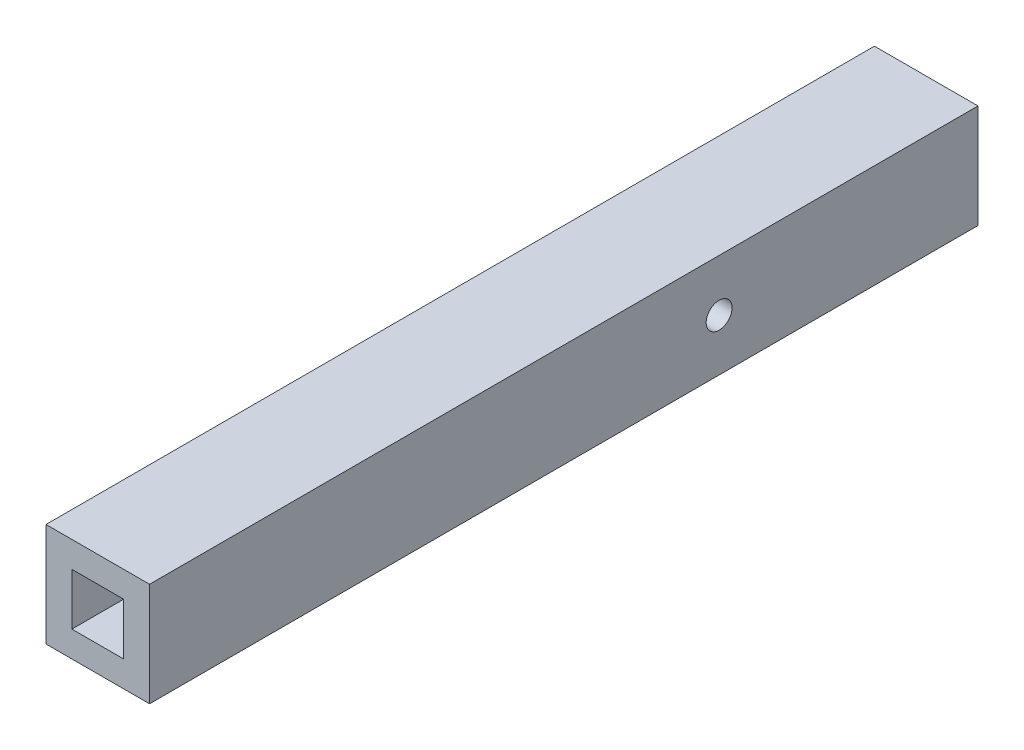
SolidWorks part; units mm, degrees
ref_plane "Front Plane" through (0, 0, 0) normal (0, 0, 1) x (1, 0, 0)
ref_plane "Top Plane" through (0, 0, 0) normal (0, 1, 0) x (1, 0, 0)
ref_plane "Right Plane" through (0, 0, 0) normal (1, 0, 0) x (0, 0, -1)
sketch "Sketch1" plane through (0, 0, 0) normal (0, 0, 1) x (1, 0, 0)
  line L1 (0, 0) -> (-25.4, 0)
  line L2 (0, 0) -> (0, 25.4)
  line L3 (0, 25.4) -> (-25.4, 25.4)
  line L4 (-25.4, 0) -> (-25.4, 25.4)
  dimension "D1" = 25.4
  dimension "D2" = 25.4
extrude "Boss-Extrude1" add sketch "Sketch1" along normal blind 203.2
sketch "Sketch2" plane through (0, 0, 0) normal (1, 0, 0) x (0, 0, -1)
  line L0 (0, 0) -> (0, 25.4) construction
  circle A0 centre (-63.5, 12.7) radius 3.175
  dimension "D1" = 6.35
  dimension "D2" = 63.5
extrude "Cut-Extrude1" cut sketch "Sketch2" against normal through all
sketch "Sketch3" plane through (0, 0, 0) normal (0, 0, -1) x (-1, 0, 0)
  line L0 (0, 25.4) -> (25.4, 25.4) construction
  line L1 (6.35, 19.05) -> (19.05, 19.05)
  line L2 (6.35, 19.05) -> (6.35, 6.35)
  line L3 (6.35, 6.35) -> (19.05, 6.35)
  line L4 (19.05, 19.05) -> (19.05, 6.35)
  line L5 (0, 0) -> (0, 25.4) construction
  line L6 (25.4, 0) -> (0, 0) construction
  line L7 (25.4, 25.4) -> (25.4, 0) construction
  dimension "D1" = 6.35
  dimension "D2" = 6.35
  dimension "D3" = 6.35
  dimension "D4" = 6.35
extrude "Cut-Extrude2" cut sketch "Sketch3" against normal through all
